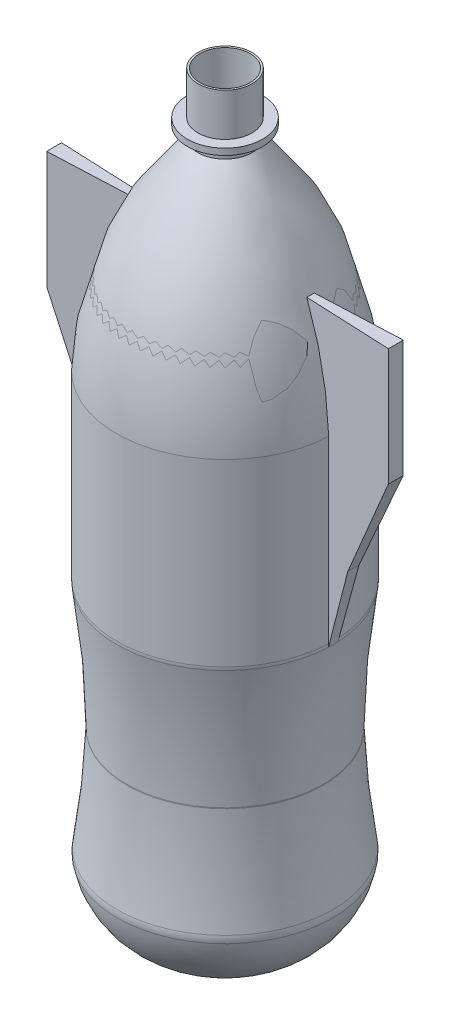
SolidWorks part; units mm, degrees
material "PET"
ref_plane "Front Plane" through (0, 0, 0) normal (0, 0, 1) x (1, 0, 0)
ref_plane "Top Plane" through (0, 0, 0) normal (0, 1, 0) x (1, 0, 0)
ref_plane "Right Plane" through (0, 0, 0) normal (1, 0, 0) x (0, 0, -1)
sketch "Sketch2" plane through (0, 0, 0) normal (0, 0, 1) x (1, 0, 0)
  line L2 (0, 16) -> (0, 16.9016)
  line L3 (11.8, 348) -> (12.7, 348)
  line L4 (50, 140.7724) -> (50, 224.9847)
  line L5 (11.8, 319.6552) -> (11.8, 325.9)
  line L6 (11.8, 325.9) -> (16.8, 325.9)
  line L7 (16.8, 325.9) -> (16.8, 327.1)
  line L8 (50.9, 140.7724) -> (50.9, 225)
  line L9 (12.7, 325) -> (17.7, 325)
  line L10 (17.7, 325) -> (17.7, 328)
  line L11 (12.7, 320) -> (12.7, 325)
  line L12 (17.7, 328) -> (12.7, 328)
  line L13 (12.7, 328) -> (12.7, 348)
  line L14 (16.8, 327.1) -> (11.8, 327.1)
  line L15 (11.8, 327.1) -> (11.8, 348)
  line L16 (-0.9, 0) -> (-0.9, 16.8364) construction
  line L17 (0, 0) -> (0, 16) construction
  line L18 (0, 0) -> (0, 9.6985)
  arc A0 (28.5036, 2.3199) -> (0, 16) centre (1.965, -16.4405) ccw
  arc A1 (32.5777, 1.5295) -> (50.5868, 28.1528) centre (10.4347, 35.9107) ccw
  arc A2 (32.5777, 1.5295) -> (28.5036, 2.3199) centre (30.9533, 4.0517) cw
  arc A3 (50.6493, 31.5888) -> (46.1064, 79.8083) centre (445.8838, 93.1488) cw
  arc A4 (46.1009, 80.1918) -> (50.7828, 139.2461) centre (446.0959, 78.1923) cw
  arc A5 (50.9, 225) -> (12.7, 320) centre (-99.0133, 219.8993) ccw
  arc A6 (50.9, 140.7724) -> (50.7828, 139.2461) centre (40.9, 140.7724) cw
  arc A7 (46.1064, 79.8083) -> (46.1009, 80.1918) centre (56.1008, 80.1418) cw
  arc A8 (50.6493, 31.5888) -> (50.5868, 28.1528) centre (40.7684, 30.0498) cw
  arc A9 (29.2385, 2.8395) -> (0, 16.9016) centre (1.965, -16.4405) ccw
  arc A10 (32.0904, 2.2862) -> (29.2385, 2.8395) centre (30.9533, 4.0517) cw
  arc A11 (32.0904, 2.2862) -> (49.7032, 28.3235) centre (10.4347, 35.9107) ccw
  arc A12 (49.76, 31.4503) -> (49.7032, 28.3235) centre (40.7684, 30.0498) cw
  arc A13 (49.76, 31.4503) -> (45.2069, 79.7783) centre (445.8838, 93.1488) cw
  arc A14 (45.2069, 79.7783) -> (45.2009, 80.1963) centre (56.1008, 80.1418) cw
  arc A15 (45.2009, 80.1963) -> (49.8934, 139.3835) centre (446.0959, 78.1923) cw
  arc A16 (50, 140.7724) -> (49.8934, 139.3835) centre (40.9, 140.7724) cw
  arc A17 (50, 224.9847) -> (11.8, 319.6552) centre (-99.0133, 219.8993) ccw
  arc A18 (29.2385, 2.8395) -> (-0.9, 16.8364) centre (1.965, -16.4405) ccw construction
  point P26 (50.9, 140)
  point P29 (46.1, 80)
  point P32 (50.9, 30)
  dimension "D3" = 32.5
  dimension "D4" = 40.8947
  dimension "D5" = 3
  dimension "D8" = 400
  dimension "D10" = 400
  dimension "D15" = 150
  dimension "D18" = 10
  dimension "D2" = 0.9
  dimension "D12" = 85
  dimension "D13" = 5
  dimension "D14" = 3
  dimension "D16" = 5
  dimension "D17" = 20
revolve "Revolve1" add sketch "Sketch2" angle 360 about L18
sketch "Sketch3" plane through (0, 0, 0) normal (0, 0, 1) x (1, 0, 0)
  line L0 (-40.157, 275.8604) -> (-80.157, 275.8604)
  line L1 (-80.157, 275.8604) -> (-80.157, 220.8604)
  line L2 (-40.157, 275.8604) -> (-55.157, 275.8604)
  line L3 (-80.157, 220.8604) -> (-60.2595, 174.99)
  line L4 (-60.2595, 174.99) -> (-50.7828, 139.2461)
  line L5 (-50.7828, 139.2461) -> (-50.9, 225)
  line L6 (0, 140.7724) -> (0, 275.8604)
  line L8 (50.7828, 139.2461) -> (50.9, 225)
  line L9 (60.2595, 174.99) -> (50.7828, 139.2461)
  line L10 (80.157, 220.8604) -> (60.2595, 174.99)
  line L11 (80.157, 275.8604) -> (80.157, 220.8604)
  line L12 (40.157, 275.8604) -> (80.157, 275.8604)
  line L13 (50.9, 140.7724) -> (-50.9, 140.7724) construction
  arc A0 (-12.7, 320) -> (-50.9, 225) centre (99.0133, 219.8993) ccw construction
  arc A1 (-50.9, 225) -> (-40.157, 275.8604) centre (99.0133, 219.8993) cw
  arc A2 (50.9, 225) -> (40.157, 275.8604) centre (-99.0133, 219.8993) ccw
  dimension "D1" = 40
  dimension "D2" = 55
  dimension "D3" = 15
  dimension "D4" = 50
revolve "Revolve2" add sketch "Sketch3" angle 2.5 about L6 other way angle 2.5
